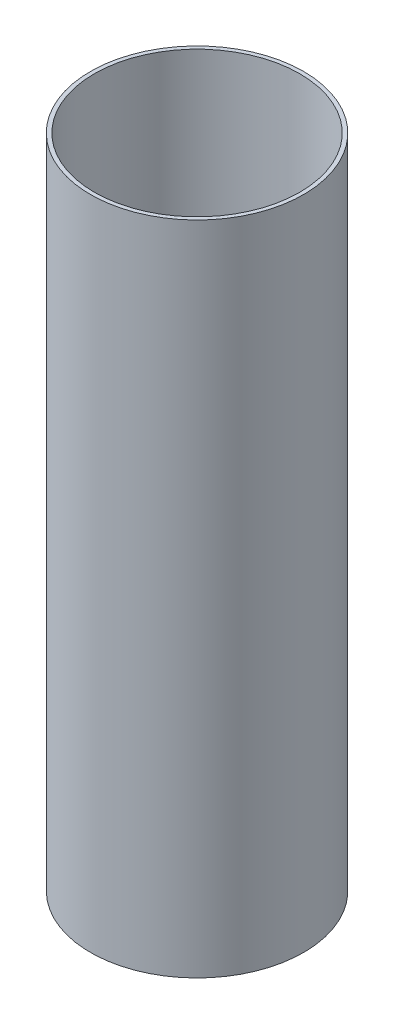
SolidWorks part; units mm, degrees
material "Wound G12 Fiberglass"
ref_plane "Front Plane" through (0, 0, 0) normal (0, 0, 1) x (1, 0, 0)
ref_plane "Top Plane" through (0, 0, 0) normal (0, 1, 0) x (1, 0, 0)
ref_plane "Right Plane" through (0, 0, 0) normal (1, 0, 0) x (0, 0, -1)
sketch "Sketch2" plane through (0, 0, 0) normal (0, 1, 0) x (1, 0, 0)
  circle A0 centre (0, 0) radius 47.6885
  circle A1 centre (0, 0) radius 49.5046
  dimension "D1" = 99.0092
  dimension "D2" = 95.377
extrude "Boss-Extrude1" add sketch "Sketch2" along normal blind 304.8
